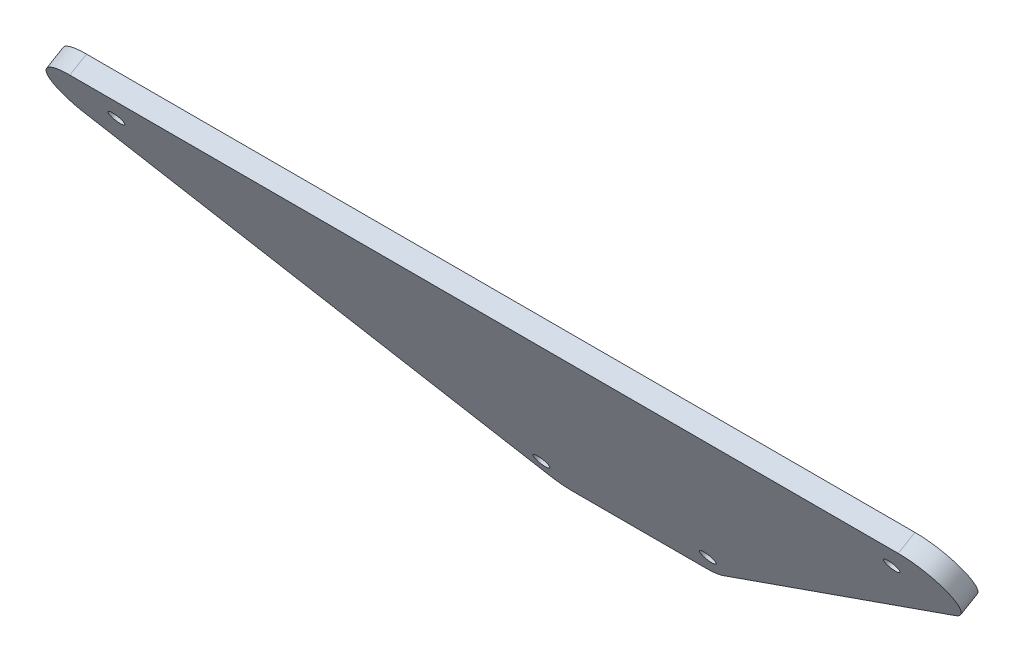
SolidWorks part; units mm, degrees
ref_plane "Front Plane" through (0, 0, 0) normal (0, 0, 1) x (1, 0, 0)
ref_plane "Top Plane" through (0, 0, 0) normal (0, 1, 0) x (1, 0, 0)
ref_plane "Right Plane" through (0, 0, 0) normal (1, 0, 0) x (0, 0, -1)
sketch "Sketch1" plane through (0, -119.4123, 203.1754) normal (0, 0.5067, -0.8621) x (-1, 0, 0)
  line L0 (-12.4918, 788.1737) -> (-176.3267, 895.9417) construction
  line L1 (-28.5797, 798.7561) -> (-142.6558, 873.7936)
  line L2 (176.3267, 895.9417) -> (12.4918, 788.1737) construction
  line L3 (142.6558, 873.7936) -> (28.5797, 798.7561)
  line L4 (-135.6765, 897.1039) -> (135.6765, 897.1039)
  line L6 (-160.0992, 897.1039) -> (160.0992, 897.1039) construction
  line L7 (-21.6003, 796.6664) -> (21.6003, 796.6664)
  arc A0 (-135.6765, 897.1039) -> (-142.6558, 873.7936) centre (-135.6765, 884.4039) ccw
  arc A1 (135.6765, 897.1039) -> (142.6558, 873.7936) centre (135.6765, 884.4039) cw
  circle A2 centre (-27.2422, 806.1914) radius 2.4892
  circle A3 centre (27.2422, 806.1914) radius 2.4892
  arc A4 (21.6003, 796.6664) -> (28.5797, 798.7561) centre (21.6003, 809.3664) ccw
  arc A5 (-21.6003, 796.6664) -> (-28.5797, 798.7561) centre (-21.6003, 809.3664) cw
  circle A6 centre (-127, 884.165) radius 2.4892
  circle A7 centre (127, 884.165) radius 2.4892
  point P15 (27.2422, 806.1914)
  dimension "D1" = 12.7
  dimension "D3" = 4.9784
  dimension "D4" = 12.7
  dimension "D2" = 9.525
extrude "Boss-Extrude1" add sketch "Sketch1" along normal blind 6.35
